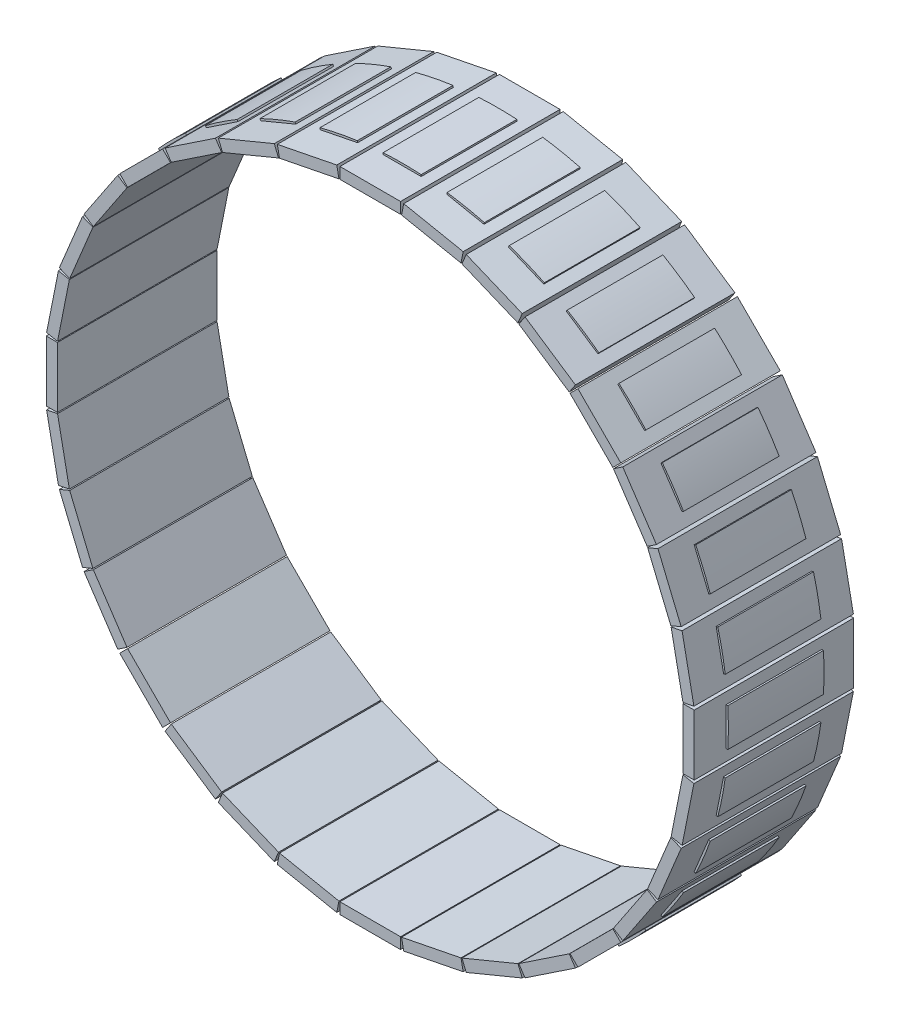
SolidWorks part; units mm, degrees
material "Никель"
ref_plane "Спереди" through (0, 0, 0) normal (0, 0, 1) x (1, 0, 0)
ref_plane "Сверху" through (0, 0, 0) normal (0, 1, 0) x (1, 0, 0)
ref_plane "Справа" through (0, 0, 0) normal (1, 0, 0) x (0, 0, -1)
sketch "Эскиз1" plane through (0, 0, 0) normal (0, 0, 1) x (1, 0, 0)
  line L1 (-9.5, 101.5566) -> (9.5, 101.5566)
  line L2 (-9.5, 101.5566) -> (-9.5, 98.0566)
  line L3 (-9.5, 98.0566) -> (9.5, 98.0566)
  line L4 (9.5, 101.5566) -> (9.5, 98.0566)
  line L5 (0, 98.0566) -> (0, 101.5566) construction
  line L6 (-9.5, 99.8066) -> (9.5, 99.8066) construction
  line L130 (10.4953, 101.4586) -> (9.8124, 98.0259)
  line L131 (10.4953, 101.4586) -> (29.1302, 97.7519)
  line L132 (29.1302, 97.7519) -> (28.4474, 94.3191)
  line L133 (9.8124, 98.0259) -> (28.4474, 94.3191)
  line L134 (30.0872, 97.4616) -> (28.7478, 94.228)
  line L135 (30.0872, 97.4616) -> (47.6409, 90.1906)
  line L136 (47.6409, 90.1906) -> (46.3015, 86.957)
  line L137 (28.7478, 94.228) -> (46.3015, 86.957)
  line L138 (48.5229, 89.7192) -> (46.5784, 86.809)
  line L139 (48.5229, 89.7192) -> (64.3208, 79.1633)
  line L140 (64.3208, 79.1633) -> (62.3763, 76.2532)
  line L141 (46.5784, 86.809) -> (62.3763, 76.2532)
  line L142 (65.0939, 78.5289) -> (62.619, 76.054)
  line L143 (65.0939, 78.5289) -> (78.5289, 65.0939)
  line L144 (78.5289, 65.0939) -> (76.054, 62.619)
  line L145 (62.619, 76.054) -> (76.054, 62.619)
  line L146 (79.1633, 64.3208) -> (76.2532, 62.3763)
  line L147 (79.1633, 64.3208) -> (89.7192, 48.5229)
  line L148 (89.7192, 48.5229) -> (86.809, 46.5784)
  line L149 (76.2532, 62.3763) -> (86.809, 46.5784)
  line L150 (90.1906, 47.6409) -> (86.957, 46.3015)
  line L151 (90.1906, 47.6409) -> (97.4616, 30.0872)
  line L152 (97.4616, 30.0872) -> (94.228, 28.7478)
  line L153 (86.957, 46.3015) -> (94.228, 28.7478)
  line L154 (97.7519, 29.1302) -> (94.3191, 28.4474)
  line L155 (97.7519, 29.1302) -> (101.4586, 10.4953)
  line L156 (101.4586, 10.4953) -> (98.0259, 9.8124)
  line L157 (94.3191, 28.4474) -> (98.0259, 9.8124)
  line L158 (101.5566, 9.5) -> (98.0566, 9.5)
  line L159 (101.5566, 9.5) -> (101.5566, -9.5)
  line L160 (101.5566, -9.5) -> (98.0566, -9.5)
  line L161 (98.0566, 9.5) -> (98.0566, -9.5)
  line L162 (101.4586, -10.4953) -> (98.0259, -9.8124)
  line L163 (101.4586, -10.4953) -> (97.7519, -29.1302)
  line L164 (97.7519, -29.1302) -> (94.3191, -28.4474)
  line L165 (98.0259, -9.8124) -> (94.3191, -28.4474)
  line L166 (97.4616, -30.0872) -> (94.228, -28.7478)
  line L167 (97.4616, -30.0872) -> (90.1906, -47.6409)
  line L168 (90.1906, -47.6409) -> (86.957, -46.3015)
  line L169 (94.228, -28.7478) -> (86.957, -46.3015)
  line L170 (89.7192, -48.5229) -> (86.809, -46.5784)
  line L171 (89.7192, -48.5229) -> (79.1633, -64.3208)
  line L172 (79.1633, -64.3208) -> (76.2532, -62.3763)
  line L173 (86.809, -46.5784) -> (76.2532, -62.3763)
  line L174 (78.5289, -65.0939) -> (76.054, -62.619)
  line L175 (78.5289, -65.0939) -> (65.0939, -78.5289)
  line L176 (65.0939, -78.5289) -> (62.619, -76.054)
  line L177 (76.054, -62.619) -> (62.619, -76.054)
  line L178 (64.3208, -79.1633) -> (62.3763, -76.2532)
  line L179 (64.3208, -79.1633) -> (48.5229, -89.7192)
  line L180 (48.5229, -89.7192) -> (46.5784, -86.809)
  line L181 (62.3763, -76.2532) -> (46.5784, -86.809)
  line L182 (47.6409, -90.1906) -> (46.3015, -86.957)
  line L183 (47.6409, -90.1906) -> (30.0872, -97.4616)
  line L184 (30.0872, -97.4616) -> (28.7478, -94.228)
  line L185 (46.3015, -86.957) -> (28.7478, -94.228)
  line L186 (29.1302, -97.7519) -> (28.4474, -94.3191)
  line L187 (29.1302, -97.7519) -> (10.4953, -101.4586)
  line L188 (10.4953, -101.4586) -> (9.8124, -98.0259)
  line L189 (28.4474, -94.3191) -> (9.8124, -98.0259)
  line L190 (9.5, -101.5566) -> (9.5, -98.0566)
  line L191 (9.5, -101.5566) -> (-9.5, -101.5566)
  line L192 (-9.5, -101.5566) -> (-9.5, -98.0566)
  line L193 (9.5, -98.0566) -> (-9.5, -98.0566)
  line L194 (-10.4953, -101.4586) -> (-9.8124, -98.0259)
  line L195 (-10.4953, -101.4586) -> (-29.1302, -97.7519)
  line L196 (-29.1302, -97.7519) -> (-28.4474, -94.3191)
  line L197 (-9.8124, -98.0259) -> (-28.4474, -94.3191)
  line L198 (-30.0872, -97.4616) -> (-28.7478, -94.228)
  line L199 (-30.0872, -97.4616) -> (-47.6409, -90.1906)
  line L200 (-47.6409, -90.1906) -> (-46.3015, -86.957)
  line L201 (-28.7478, -94.228) -> (-46.3015, -86.957)
  line L202 (-48.5229, -89.7192) -> (-46.5784, -86.809)
  line L203 (-48.5229, -89.7192) -> (-64.3208, -79.1633)
  line L204 (-64.3208, -79.1633) -> (-62.3763, -76.2532)
  line L205 (-46.5784, -86.809) -> (-62.3763, -76.2532)
  line L206 (-65.0939, -78.5289) -> (-62.619, -76.054)
  line L207 (-65.0939, -78.5289) -> (-78.5289, -65.0939)
  line L208 (-78.5289, -65.0939) -> (-76.054, -62.619)
  line L209 (-62.619, -76.054) -> (-76.054, -62.619)
  line L210 (-79.1633, -64.3208) -> (-76.2532, -62.3763)
  line L211 (-79.1633, -64.3208) -> (-89.7192, -48.5229)
  line L212 (-89.7192, -48.5229) -> (-86.809, -46.5784)
  line L213 (-76.2532, -62.3763) -> (-86.809, -46.5784)
  line L214 (-90.1906, -47.6409) -> (-86.957, -46.3015)
  line L215 (-90.1906, -47.6409) -> (-97.4616, -30.0872)
  line L216 (-97.4616, -30.0872) -> (-94.228, -28.7478)
  line L217 (-86.957, -46.3015) -> (-94.228, -28.7478)
  line L218 (-97.7519, -29.1302) -> (-94.3191, -28.4474)
  line L219 (-97.7519, -29.1302) -> (-101.4586, -10.4953)
  line L220 (-101.4586, -10.4953) -> (-98.0259, -9.8124)
  line L221 (-94.3191, -28.4474) -> (-98.0259, -9.8124)
  line L222 (-101.5566, -9.5) -> (-98.0566, -9.5)
  line L223 (-101.5566, -9.5) -> (-101.5566, 9.5)
  line L224 (-101.5566, 9.5) -> (-98.0566, 9.5)
  line L225 (-98.0566, -9.5) -> (-98.0566, 9.5)
  line L226 (-101.4586, 10.4953) -> (-98.0259, 9.8124)
  line L227 (-101.4586, 10.4953) -> (-97.7519, 29.1302)
  line L228 (-97.7519, 29.1302) -> (-94.3191, 28.4474)
  line L229 (-98.0259, 9.8124) -> (-94.3191, 28.4474)
  line L230 (-97.4616, 30.0872) -> (-94.228, 28.7478)
  line L231 (-97.4616, 30.0872) -> (-90.1906, 47.6409)
  line L232 (-90.1906, 47.6409) -> (-86.957, 46.3015)
  line L233 (-94.228, 28.7478) -> (-86.957, 46.3015)
  line L234 (-89.7192, 48.5229) -> (-86.809, 46.5784)
  line L235 (-89.7192, 48.5229) -> (-79.1633, 64.3208)
  line L236 (-79.1633, 64.3208) -> (-76.2532, 62.3763)
  line L237 (-86.809, 46.5784) -> (-76.2532, 62.3763)
  line L238 (-78.5289, 65.0939) -> (-76.054, 62.619)
  line L239 (-78.5289, 65.0939) -> (-65.0939, 78.5289)
  line L240 (-65.0939, 78.5289) -> (-62.619, 76.054)
  line L241 (-76.054, 62.619) -> (-62.619, 76.054)
  line L242 (-64.3208, 79.1633) -> (-62.3763, 76.2532)
  line L243 (-64.3208, 79.1633) -> (-48.5229, 89.7192)
  line L244 (-48.5229, 89.7192) -> (-46.5784, 86.809)
  line L245 (-62.3763, 76.2532) -> (-46.5784, 86.809)
  line L246 (-47.6409, 90.1906) -> (-46.3015, 86.957)
  line L247 (-47.6409, 90.1906) -> (-30.0872, 97.4616)
  line L248 (-30.0872, 97.4616) -> (-28.7478, 94.228)
  line L249 (-46.3015, 86.957) -> (-28.7478, 94.228)
  line L250 (-29.1302, 97.7519) -> (-28.4474, 94.3191)
  line L251 (-29.1302, 97.7519) -> (-10.4953, 101.4586)
  line L252 (-10.4953, 101.4586) -> (-9.8124, 98.0259)
  line L253 (-28.4474, 94.3191) -> (-9.8124, 98.0259)
  circle A0 centre (0, 0) radius 102 construction
  point P3 (0, 99.8066)
  point P139 (-0.2511, -0.2511)
  point P140 (0, 0)
  dimension "D1" = 204
  dimension "D2" = 32
  dimension "D3" = 19
extrude "Бобышка-Вытянуть1" add sketch "Эскиз1" along normal blind 50
sketch "Эскиз2" plane through (0, 0, 50) normal (0, 0, 1) x (1, 0, 0)
  line L0 (-5.9657, 102.0758) -> (-5.9657, 100.5331)
  line L1 (-5.9657, 100.5331) -> (5.9657, 100.5331)
  line L2 (5.9657, 100.5331) -> (5.9657, 102.0758)
  line L3 (0, 98.0566) -> (0, 105.2003) construction
  line L4 (-9.5, 98.0566) -> (9.5, 98.0566) construction
  line L5 (25.4641, 97.4375) -> (25.7651, 98.9506)
  line L6 (14.0629, 101.2783) -> (13.762, 99.7652)
  line L7 (13.762, 99.7652) -> (25.4641, 97.4375)
  line L8 (43.9839, 90.5975) -> (44.5743, 92.0228)
  line L9 (33.5511, 96.5887) -> (32.9608, 95.1634)
  line L10 (32.9608, 95.1634) -> (43.9839, 90.5975)
  line L11 (60.8135, 80.2758) -> (61.6706, 81.5586)
  line L12 (51.75, 88.1873) -> (50.8929, 86.9046)
  line L13 (50.8929, 86.9046) -> (60.8135, 80.2758)
  line L14 (75.306, 66.8692) -> (76.3969, 67.9601)
  line L15 (67.9601, 76.3969) -> (66.8692, 75.306)
  line L16 (66.8692, 75.306) -> (75.306, 66.8692)
  line L17 (86.9046, 50.8929) -> (88.1873, 51.75)
  line L18 (81.5586, 61.6706) -> (80.2758, 60.8135)
  line L19 (80.2758, 60.8135) -> (86.9046, 50.8929)
  line L20 (95.1634, 32.9608) -> (96.5887, 33.5511)
  line L21 (92.0228, 44.5743) -> (90.5975, 43.9839)
  line L22 (90.5975, 43.9839) -> (95.1634, 32.9608)
  line L23 (99.7652, 13.762) -> (101.2783, 14.0629)
  line L24 (98.9506, 25.7651) -> (97.4375, 25.4641)
  line L25 (97.4375, 25.4641) -> (99.7652, 13.762)
  line L26 (100.5331, -5.9657) -> (102.0758, -5.9657)
  line L27 (102.0758, 5.9657) -> (100.5331, 5.9657)
  line L28 (100.5331, 5.9657) -> (100.5331, -5.9657)
  line L29 (97.4375, -25.4641) -> (98.9506, -25.7651)
  line L30 (101.2783, -14.0629) -> (99.7652, -13.762)
  line L31 (99.7652, -13.762) -> (97.4375, -25.4641)
  line L32 (90.5975, -43.9839) -> (92.0228, -44.5743)
  line L33 (96.5887, -33.5511) -> (95.1634, -32.9608)
  line L34 (95.1634, -32.9608) -> (90.5975, -43.9839)
  line L35 (80.2758, -60.8135) -> (81.5586, -61.6706)
  line L36 (88.1873, -51.75) -> (86.9046, -50.8929)
  line L37 (86.9046, -50.8929) -> (80.2758, -60.8135)
  line L38 (66.8692, -75.306) -> (67.9601, -76.3969)
  line L39 (76.3969, -67.9601) -> (75.306, -66.8692)
  line L40 (75.306, -66.8692) -> (66.8692, -75.306)
  line L41 (50.8929, -86.9046) -> (51.75, -88.1873)
  line L42 (61.6706, -81.5586) -> (60.8135, -80.2758)
  line L43 (60.8135, -80.2758) -> (50.8929, -86.9046)
  line L44 (32.9608, -95.1634) -> (33.5511, -96.5887)
  line L45 (44.5743, -92.0228) -> (43.9839, -90.5975)
  line L46 (43.9839, -90.5975) -> (32.9608, -95.1634)
  line L47 (13.762, -99.7652) -> (14.0629, -101.2783)
  line L48 (25.7651, -98.9506) -> (25.4641, -97.4375)
  line L49 (25.4641, -97.4375) -> (13.762, -99.7652)
  line L50 (-5.9657, -100.5331) -> (-5.9657, -102.0758)
  line L51 (5.9657, -102.0758) -> (5.9657, -100.5331)
  line L52 (5.9657, -100.5331) -> (-5.9657, -100.5331)
  line L53 (-25.4641, -97.4375) -> (-25.7651, -98.9506)
  line L54 (-14.0629, -101.2783) -> (-13.762, -99.7652)
  line L55 (-13.762, -99.7652) -> (-25.4641, -97.4375)
  line L56 (-43.9839, -90.5975) -> (-44.5743, -92.0228)
  line L57 (-33.5511, -96.5887) -> (-32.9608, -95.1634)
  line L58 (-32.9608, -95.1634) -> (-43.9839, -90.5975)
  line L59 (-60.8135, -80.2758) -> (-61.6706, -81.5586)
  line L60 (-51.75, -88.1873) -> (-50.8929, -86.9046)
  line L61 (-50.8929, -86.9046) -> (-60.8135, -80.2758)
  line L62 (-75.306, -66.8692) -> (-76.3969, -67.9601)
  line L63 (-67.9601, -76.3969) -> (-66.8692, -75.306)
  line L64 (-66.8692, -75.306) -> (-75.306, -66.8692)
  line L65 (-86.9046, -50.8929) -> (-88.1873, -51.75)
  line L66 (-81.5586, -61.6706) -> (-80.2758, -60.8135)
  line L67 (-80.2758, -60.8135) -> (-86.9046, -50.8929)
  line L68 (-95.1634, -32.9608) -> (-96.5887, -33.5511)
  line L69 (-92.0228, -44.5743) -> (-90.5975, -43.9839)
  line L70 (-90.5975, -43.9839) -> (-95.1634, -32.9608)
  line L71 (-99.7652, -13.762) -> (-101.2783, -14.0629)
  line L72 (-98.9506, -25.7651) -> (-97.4375, -25.4641)
  line L73 (-97.4375, -25.4641) -> (-99.7652, -13.762)
  line L74 (-100.5331, 5.9657) -> (-102.0758, 5.9657)
  line L75 (-102.0758, -5.9657) -> (-100.5331, -5.9657)
  line L76 (-100.5331, -5.9657) -> (-100.5331, 5.9657)
  line L77 (-97.4375, 25.4641) -> (-98.9506, 25.7651)
  line L78 (-101.2783, 14.0629) -> (-99.7652, 13.762)
  line L79 (-99.7652, 13.762) -> (-97.4375, 25.4641)
  line L80 (-90.5975, 43.9839) -> (-92.0228, 44.5743)
  line L81 (-96.5887, 33.5511) -> (-95.1634, 32.9608)
  line L82 (-95.1634, 32.9608) -> (-90.5975, 43.9839)
  line L83 (-80.2758, 60.8135) -> (-81.5586, 61.6706)
  line L84 (-88.1873, 51.75) -> (-86.9046, 50.8929)
  line L85 (-86.9046, 50.8929) -> (-80.2758, 60.8135)
  line L86 (-66.8692, 75.306) -> (-67.9601, 76.3969)
  line L87 (-76.3969, 67.9601) -> (-75.306, 66.8692)
  line L88 (-75.306, 66.8692) -> (-66.8692, 75.306)
  line L89 (-50.8929, 86.9046) -> (-51.75, 88.1873)
  line L90 (-61.6706, 81.5586) -> (-60.8135, 80.2758)
  line L91 (-60.8135, 80.2758) -> (-50.8929, 86.9046)
  line L92 (-32.9608, 95.1634) -> (-33.5511, 96.5887)
  line L93 (-44.5743, 92.0228) -> (-43.9839, 90.5975)
  line L94 (-43.9839, 90.5975) -> (-32.9608, 95.1634)
  line L95 (-13.762, 99.7652) -> (-14.0629, 101.2783)
  line L96 (-25.7651, 98.9506) -> (-25.4641, 97.4375)
  line L97 (-25.4641, 97.4375) -> (-13.762, 99.7652)
  circle A0 centre (0, 0) radius 102.25 construction
  arc A1 (-5.9657, 102.0758) -> (5.9657, 102.0758) centre (0, 0) cw
  arc A2 (14.0629, 101.2783) -> (25.7651, 98.9506) centre (0, 0) cw
  arc A3 (33.5511, 96.5887) -> (44.5743, 92.0228) centre (0, 0) cw
  arc A4 (51.75, 88.1873) -> (61.6706, 81.5586) centre (0, 0) cw
  arc A5 (67.9601, 76.3969) -> (76.3969, 67.9601) centre (0, 0) cw
  arc A6 (81.5586, 61.6706) -> (88.1873, 51.75) centre (0, 0) cw
  arc A7 (92.0228, 44.5743) -> (96.5887, 33.5511) centre (0, 0) cw
  arc A8 (98.9506, 25.7651) -> (101.2783, 14.0629) centre (0, 0) cw
  arc A9 (102.0758, 5.9657) -> (102.0758, -5.9657) centre (0, 0) cw
  arc A10 (101.2783, -14.0629) -> (98.9506, -25.7651) centre (0, 0) cw
  arc A11 (96.5887, -33.5511) -> (92.0228, -44.5743) centre (0, 0) cw
  arc A12 (88.1873, -51.75) -> (81.5586, -61.6706) centre (0, 0) cw
  arc A13 (76.3969, -67.9601) -> (67.9601, -76.3969) centre (0, 0) cw
  arc A14 (61.6706, -81.5586) -> (51.75, -88.1873) centre (0, 0) cw
  arc A15 (44.5743, -92.0228) -> (33.5511, -96.5887) centre (0, 0) cw
  arc A16 (25.7651, -98.9506) -> (14.0629, -101.2783) centre (0, 0) cw
  arc A17 (5.9657, -102.0758) -> (-5.9657, -102.0758) centre (0, 0) cw
  arc A18 (-14.0629, -101.2783) -> (-25.7651, -98.9506) centre (0, 0) cw
  arc A19 (-33.5511, -96.5887) -> (-44.5743, -92.0228) centre (0, 0) cw
  arc A20 (-51.75, -88.1873) -> (-61.6706, -81.5586) centre (0, 0) cw
  arc A21 (-67.9601, -76.3969) -> (-76.3969, -67.9601) centre (0, 0) cw
  arc A22 (-81.5586, -61.6706) -> (-88.1873, -51.75) centre (0, 0) cw
  arc A23 (-92.0228, -44.5743) -> (-96.5887, -33.5511) centre (0, 0) cw
  arc A24 (-98.9506, -25.7651) -> (-101.2783, -14.0629) centre (0, 0) cw
  arc A25 (-102.0758, -5.9657) -> (-102.0758, 5.9657) centre (0, 0) cw
  arc A26 (-101.2783, 14.0629) -> (-98.9506, 25.7651) centre (0, 0) cw
  arc A27 (-96.5887, 33.5511) -> (-92.0228, 44.5743) centre (0, 0) cw
  arc A28 (-88.1873, 51.75) -> (-81.5586, 61.6706) centre (0, 0) cw
  arc A29 (-76.3969, 67.9601) -> (-67.9601, 76.3969) centre (0, 0) cw
  arc A30 (-61.6706, 81.5586) -> (-51.75, 88.1873) centre (0, 0) cw
  arc A31 (-44.5743, 92.0228) -> (-33.5511, 96.5887) centre (0, 0) cw
  arc A32 (-25.7651, 98.9506) -> (-14.0629, 101.2783) centre (0, 0) cw
  point P12 (0, 100.5331)
  point P140 (0, 0)
  dimension "D1" = 204.5
  dimension "D2" = 32
extrude "Бобышка-Вытянуть2" add sketch "Эскиз2" against normal blind 30 from offset 10
